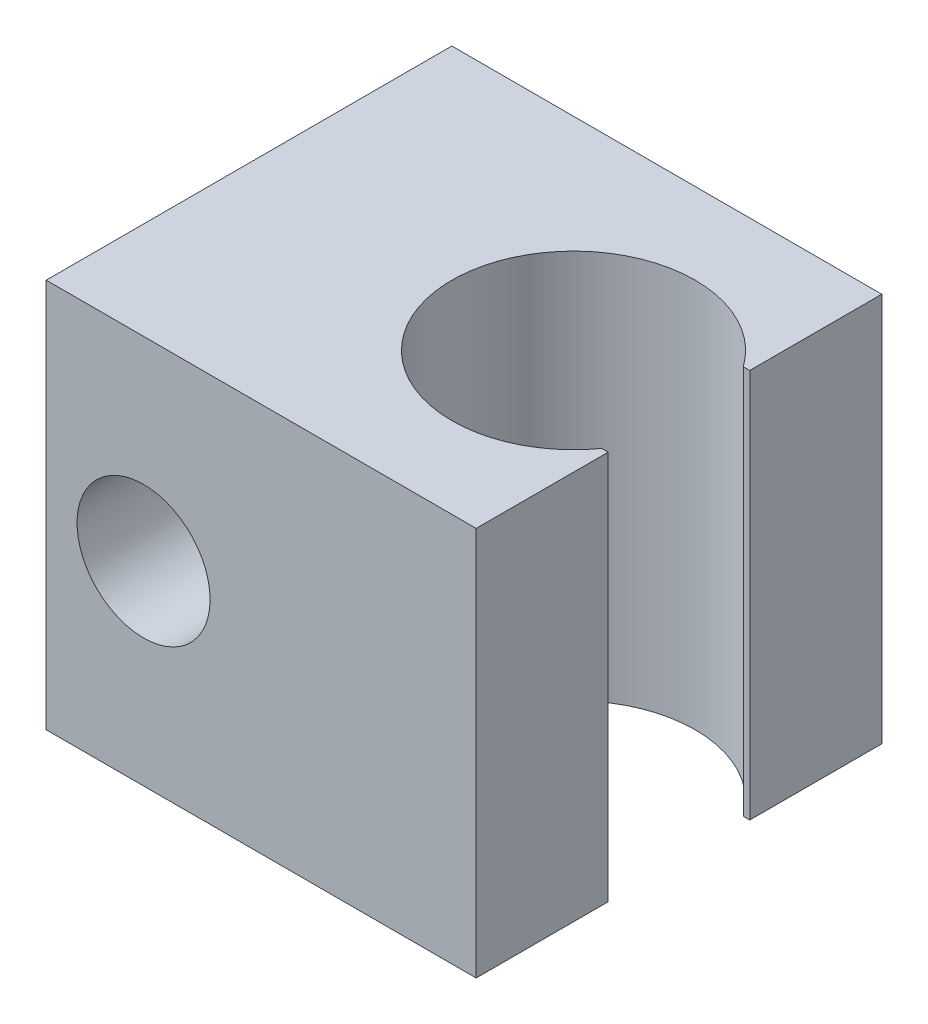
SolidWorks part; units mm, degrees
material "PET"
ref_plane "Front Plane" through (0, 0, 0) normal (0, 0, 1) x (1, 0, 0)
ref_plane "Top Plane" through (0, 0, 0) normal (0, 1, 0) x (1, 0, 0)
ref_plane "Right Plane" through (0, 0, 0) normal (1, 0, 0) x (0, 0, -1)
sketch "Sketch1" plane through (0, 0, 0) normal (0, 1, 0) x (1, 0, 0)
  line L1 (0, 12.5) -> (-10, 12.5)
  line L2 (-10, -12.5) -> (-20, -12.5)
  line L3 (0, -12.5) -> (-10, -12.5)
  line L4 (-10, 12.5) -> (-10, -12.5)
  line L5 (-10, -12.5) -> (-10, 12.5)
  line L6 (-10, 12.5) -> (-20, 12.5)
  line L7 (-20, -12.5) -> (-20, 12.5)
  line L8 (0, 12.5) -> (12.5, 12.5)
  line L10 (0, -12.5) -> (12.5, -12.5)
  line L11 (12.5, 12.5) -> (12.5, -12.5)
  circle A0 centre (0, 0) radius 7.5
  arc A1 (0, -12.5) -> (0, 12.5) centre (0, 0) ccw construction
  dimension "D1" = 15
  dimension "D2" = 12.5
  dimension "D3" = 10
  dimension "D4" = 10
extrude "Boss-Extrude1" add sketch "Sketch1" along normal blind 24 contours L3 A1 L1 L4 A0
sketch "Sketch5" plane through (0, 0, 0) normal (0, -1, 0) x (1, 0, 0)
  line L0 (12.5, -12.5) -> (12.5, 12.5) construction
  line L1 (12.5, 12.5) -> (6.5, 12.5)
  line L2 (12.5, 12.5) -> (12.5, -12.5)
  line L3 (12.5, -12.5) -> (6.5, -12.5)
  line L4 (6.5, 12.5) -> (6.5, 4.3635)
  line L6 (6.5, -4.3635) -> (6.5, -12.5)
  line L7 (6.5, 4.3635) -> (6.1, 4.3635)
  line L8 (12.5, 12.5) -> (-10, 12.5) construction
  line L9 (6.5, -4.3635) -> (6.1, -4.3635)
  line L10 (6.1, 4.3635) -> (6.1, -4.3635)
  line L11 (12.5, -12.5) -> (-10, -12.5) construction
  circle A3 centre (0, 0) radius 7.5 construction
  point P15 (6.1, 0)
  point P16 (12.5, 0)
  dimension "D1" = 6
  dimension "D2" = 0.4
  dimension "D3" = 0
extrude "Cut-Extrude4" cut sketch "Sketch5" against normal through all
sketch "Sketch7" plane through (0, 0, 0) normal (0, -1, 0) x (1, 0, 0)
  line L1 (0, 12.5) -> (-10, 12.5)
  line L2 (-10, -12.5) -> (-20, -12.5)
  line L3 (0, -12.5) -> (-10, -12.5)
  line L4 (-10, 12.5) -> (-10, -12.5)
  line L5 (-10, -12.5) -> (-10, 12.5)
  line L6 (-10, 12.5) -> (-20, 12.5)
  line L7 (-20, -12.5) -> (-20, 12.5)
  circle A0 centre (0, 0) radius 7.5
  arc A1 (0, -12.5) -> (0, 12.5) centre (0, 0) ccw
  line M21 (-10, 12.5) -> (-10, -12.5)
  dimension "D1" = 15
  dimension "D2" = 12.5
  dimension "D3" = 10
  dimension "D4" = 10
extrude "Boss-Extrude2" add sketch "Sketch7" against normal blind 24 contours L7 L2 L6 M21
sketch "Sketch8" plane through (0, 0, 12.5) normal (0, 0, 1) x (1, 0, 0)
  line L0 (-20, 12) -> (6.5, 12) construction
  line L1 (-20, 24) -> (-20, 0) construction
  line L3 (6.5, 24) -> (6.5, 0) construction
  circle A0 centre (-14, 12) radius 4.1
  dimension "D1" = 8.2
  dimension "D2" = 6
extrude "Cut-Extrude5" cut sketch "Sketch8" against normal blind 48
